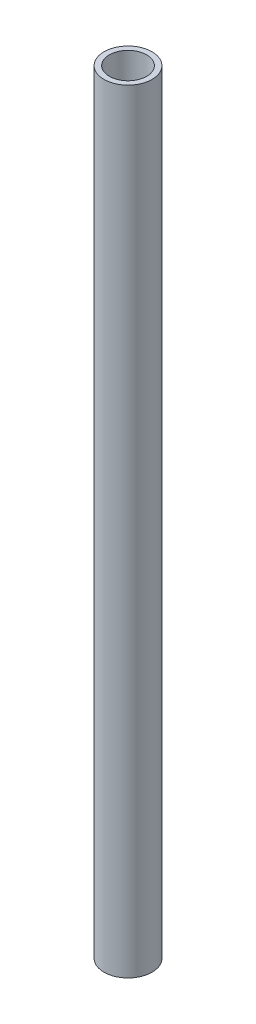
SolidWorks part; units mm, degrees
ref_plane "Front Plane" through (0, 0, 0) normal (0, 0, 1) x (1, 0, 0)
ref_plane "Top Plane" through (0, 0, 0) normal (0, 1, 0) x (1, 0, 0)
ref_plane "Right Plane" through (0, 0, 0) normal (1, 0, 0) x (0, 0, -1)
sketch "Sketch1" plane through (0, 0, 0) normal (0, 1, 0) x (1, 0, 0)
  circle A0 centre (0, 0) radius 88.9
  circle A1 centre (0, 0) radius 114.3
  dimension "D1" = 228.6
  dimension "D2" = 177.8
extrude "Boss-Extrude1" add sketch "Sketch1" along normal blind 3683
